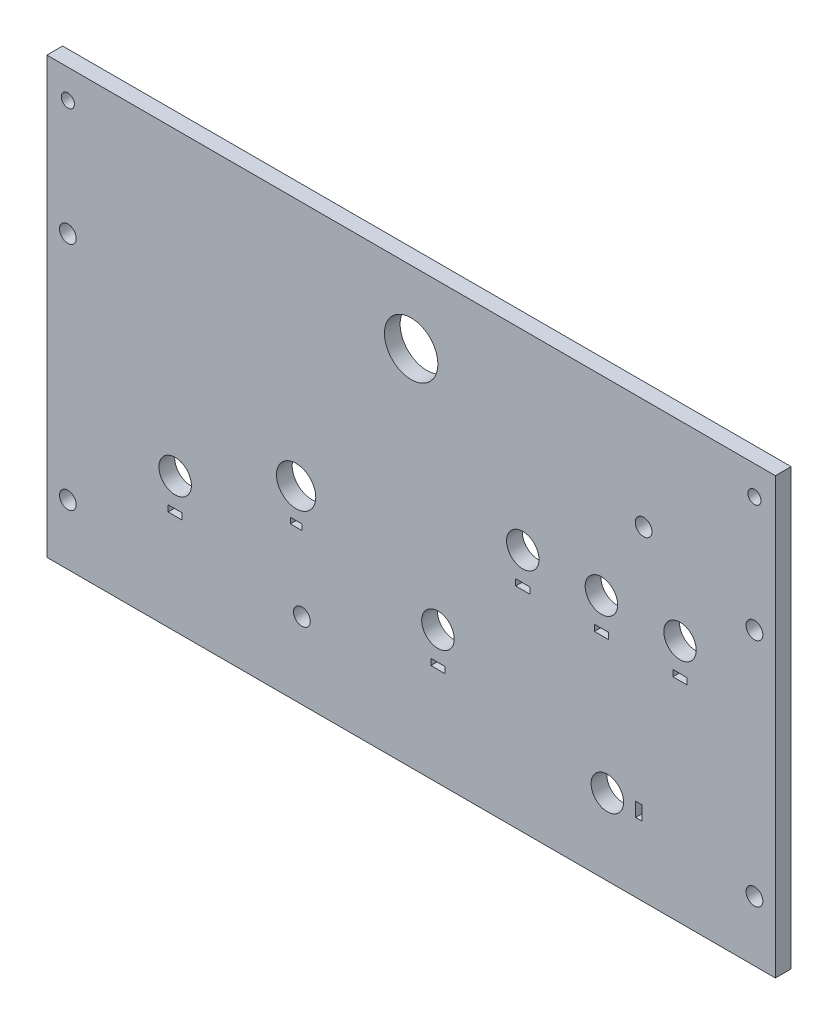
SolidWorks part; units mm, degrees
ref_plane "Front Plane" through (0, 0, 0) normal (0, 0, 1) x (1, 0, 0)
ref_plane "Top Plane" through (0, 0, 0) normal (0, 1, 0) x (1, 0, 0)
ref_plane "Right Plane" through (0, 0, 0) normal (1, 0, 0) x (0, 0, -1)
sketch "Sketch1" plane through (0, 0, 0) normal (0, 0, 1) x (1, 0, 0)
  line L0 (0, 41.5) -> (139, 41.5) construction
  line L1 (0, 0) -> (139, 0)
  line L2 (0, 0) -> (0, 83)
  line L3 (0, 83) -> (139, 83)
  line L4 (139, 0) -> (139, 83)
  line L5 (69.5, 83) -> (69.5, 0) construction
  line L17 (74.6156, 25.3611) -> (74.6156, 19.3611) construction
  line L45 (73.2656, 18.7611) -> (75.9656, 18.7611)
  line L50 (73.2656, 18.7611) -> (73.2656, 19.9611)
  line L51 (73.2656, 19.9611) -> (75.9656, 19.9611)
  line L52 (75.9656, 18.7611) -> (75.9656, 19.9611)
  line L65 (73.2656, 18.7611) -> (75.9656, 19.9611) construction
  line L66 (24.475, 25.6666) -> (24.475, 19.6666) construction
  line L67 (23.125, 19.0666) -> (25.825, 19.0666)
  line L68 (23.125, 19.0666) -> (23.125, 20.2666)
  line L69 (23.125, 20.2666) -> (25.825, 20.2666)
  line L70 (25.825, 19.0666) -> (25.825, 20.2666)
  line L71 (23.125, 19.0666) -> (25.825, 20.2666) construction
  line L72 (23.125, 20.2666) -> (25.825, 19.0666) construction
  line L80 (73.2656, 19.9611) -> (75.9656, 18.7611) construction
  line L81 (106.9326, 14.545) -> (112.9326, 14.545) construction
  line L86 (113.5326, 13.195) -> (113.5326, 15.895)
  line L87 (113.5326, 13.195) -> (112.3326, 13.195)
  line L88 (112.3326, 13.195) -> (112.3326, 15.895)
  line L89 (113.5326, 15.895) -> (112.3326, 15.895)
  line L90 (113.5326, 13.195) -> (112.3326, 15.895) construction
  line L91 (112.3326, 13.195) -> (113.5326, 15.895) construction
  line L94 (47.5544, 35.5628) -> (47.5544, 50.9276) construction
  line L95 (46.4544, 28.7628) -> (48.6544, 28.7628)
  line L96 (46.4544, 28.7628) -> (46.4544, 29.8628)
  line L97 (46.4544, 29.8628) -> (48.6544, 29.8628)
  line L98 (48.6544, 28.7628) -> (48.6544, 29.8628)
  line L99 (46.4544, 28.7628) -> (48.6544, 29.8628) construction
  line L100 (46.4544, 29.8628) -> (48.6544, 28.7628) construction
  line L101 (90.8006, 46.5969) -> (90.8006, 40.5969) construction
  line L106 (89.4506, 39.9969) -> (92.1506, 39.9969)
  line L107 (89.4506, 39.9969) -> (89.4506, 41.1969)
  line L108 (89.4506, 41.1969) -> (92.1506, 41.1969)
  line L109 (92.1506, 39.9969) -> (92.1506, 41.1969)
  line L110 (89.4506, 39.9969) -> (92.1506, 41.1969) construction
  line L111 (89.4506, 41.1969) -> (92.1506, 39.9969) construction
  line L112 (105.8006, 46.5969) -> (105.8006, 40.5969) construction
  line L113 (104.4506, 39.9969) -> (107.1506, 39.9969)
  line L114 (104.4506, 39.9969) -> (104.4506, 41.1969)
  line L115 (104.4506, 41.1969) -> (107.1506, 41.1969)
  line L116 (107.1506, 39.9969) -> (107.1506, 41.1969)
  line L117 (104.4506, 39.9969) -> (107.1506, 41.1969) construction
  line L118 (104.4506, 41.1969) -> (107.1506, 39.9969) construction
  line L119 (120.8006, 46.5969) -> (120.8006, 40.5969) construction
  line L120 (119.4506, 39.9969) -> (122.1506, 39.9969)
  line L121 (119.4506, 39.9969) -> (119.4506, 41.1969)
  line L122 (119.4506, 41.1969) -> (122.1506, 41.1969)
  line L123 (122.1506, 39.9969) -> (122.1506, 41.1969)
  line L124 (119.4506, 39.9969) -> (122.1506, 41.1969) construction
  line L125 (119.4506, 41.1969) -> (122.1506, 39.9969) construction
  circle A4 centre (4, 55.5) radius 1.6
  circle A5 centre (135, 55.5) radius 1.6
  circle A6 centre (135, 11.5) radius 1.6
  circle A7 centre (4, 11.5) radius 1.6
  circle A9 centre (48.6544, 14.545) radius 1.6
  circle A19 centre (24.475, 25.6666) radius 3.1
  circle A27 centre (135, 77.5) radius 1.25
  circle A28 centre (4, 77.5) radius 1.25
  circle A29 centre (74.6156, 25.3611) radius 3.1
  circle A30 centre (106.9326, 14.545) radius 3.1
  circle A34 centre (47.5544, 35.5628) radius 3.75
  circle A36 centre (69.5, 69.2318) radius 5.1
  circle A37 centre (113.8581, 61.9527) radius 1.6
  circle A38 centre (90.8006, 46.5969) radius 3.1
  circle A39 centre (105.8006, 46.5969) radius 3.1
  circle A40 centre (120.8006, 46.5969) radius 3.1
  point P9 (74.6156, 19.3611)
  point P27 (112.9326, 14.545)
  point P40 (47.5544, 29.3128)
  point P47 (90.8006, 40.5969)
  point P58 (105.8006, 40.5969)
  point P69 (120.8006, 40.5969)
  point P75 (0, 0)
  point P76 (0, 0)
  point P77 (109.5502, 55.539)
  point P78 (93.5442, 55.312)
  point P79 (107.9042, 55.2552)
  point P80 (121.1291, 54.9714)
  point P81 (113.5326, 69.2318)
  point P82 (120.8006, 46.5969)
  point P83 (113.8581, 61.9527)
  point P116 (24.475, 19.6666)
  dimension "D8" = 3.2
  dimension "D19" = 3.2
  dimension "D16" = 6.2
  dimension "D27" = 2.5
  dimension "D7" = 6.2
  dimension "D22" = 6.2
  dimension "D37" = 10.2
  dimension "D26" = 7.5
  dimension "D34" = 6.2
  dimension "D39" = 6.2
  dimension "D43" = 6.2
  dimension "D1" = 139
  dimension "D2" = 83
  dimension "D13" = 27.5
  dimension "D11" = 131
  dimension "D12" = 4
  dimension "D20" = 4
  dimension "D3" = 11.5
  dimension "D50" = 1.2
  dimension "D51" = 6
  dimension "D14" = 44
  dimension "D28" = 5.5
  dimension "D29" = 4
  dimension "D30" = 4
  dimension "D32" = 2.7
  dimension "D4" = 1.2
  dimension "D6" = 6
  dimension "D17" = 2.7
  dimension "D18" = 1.2
  dimension "D21" = 6
  dimension "D23" = 2.7
  dimension "D24" = 2.2
  dimension "D25" = 1.1
  dimension "D31" = 5.7
  dimension "D15" = 1.2
  dimension "D33" = 6
  dimension "D35" = 2.7
  dimension "D36" = 1.2
  dimension "D38" = 6
  dimension "D40" = 2.7
  dimension "D41" = 1.2
  dimension "D42" = 6
  dimension "D44" = 2.7
  dimension "D45" = 15
  dimension "D46" = 15
  dimension "D9" = 2
  dimension "D10" = 2
extrude "Boss-Extrude1" add sketch "Sketch1" along normal blind 3
equation "\"D13@Sketch1\"=22+5.5"
